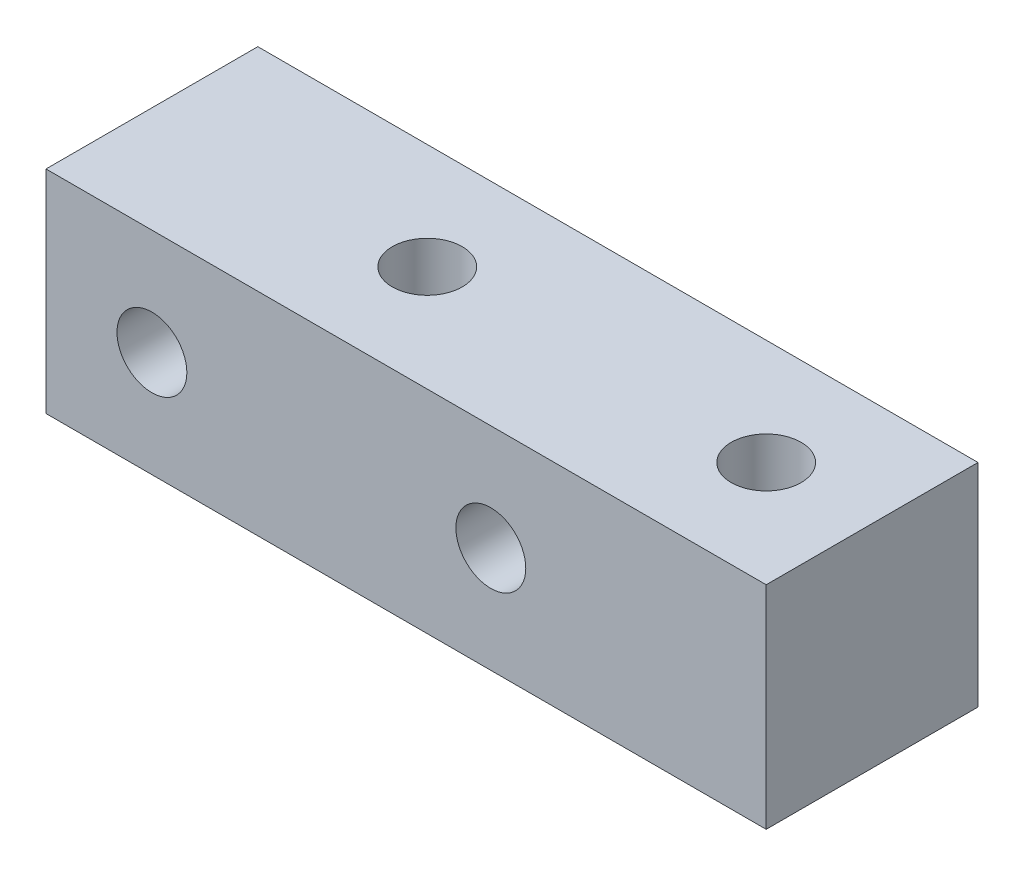
SolidWorks part; units mm, degrees
ref_plane "前视基准面" through (0, 0, 0) normal (0, 0, 1) x (1, 0, 0)
ref_plane "上视基准面" through (0, 0, 0) normal (0, 1, 0) x (1, 0, 0)
ref_plane "右视基准面" through (0, 0, 0) normal (1, 0, 0) x (0, 0, -1)
other "Configuration Table"
sketch "草图1" plane through (0, 0, 0) normal (0, 1, 0) x (1, 0, 0)
  line L1 (-17, 5) -> (17, 5)
  line L2 (-17, 5) -> (-17, -5)
  line L3 (-17, -5) -> (17, -5)
  line L4 (17, 5) -> (17, -5)
  line L5 (-17, 5) -> (17, -5) construction
  line L6 (-17, -5) -> (17, 5) construction
  point P0 (0, 0)
  dimension "D1" = 34
  dimension "D2" = 10
extrude "凸台-拉伸1" add sketch "草图1" along normal blind 10
sketch "草图2" plane through (0, 0, 5) normal (0, 0, 1) x (1, 0, 0)
  line L0 (-17, 5) -> (17, 5) construction
  line L1 (-17, 10) -> (-17, 0) construction
  line L2 (17, 10) -> (17, 0) construction
  point P6 (-12, 5)
  point P7 (4, 5)
  dimension "D1" = 16
  dimension "D2" = 5
sketch "草图4" plane through (0, 10, 0) normal (0, 1, 0) x (1, 0, 0)
  line L0 (-17, 0) -> (17, 0) construction
  line L1 (-17, 5) -> (-17, -5) construction
  line L2 (17, -5) -> (17, 5) construction
  point P6 (12, 0)
  point P7 (-4, 0)
  dimension "D1" = 5
  dimension "D2" = 16
hole_wizard "M4 螺纹孔1" positions "草图2" profile "草图3" tap size "M4" standard "GB" end condition through all
sketch "草图3" plane through (4, 5, 5) normal (1, 0, 0) x (0, -1, 0)
  line L0 (0, 0) -> (0, 10)
  line L1 (0, 10) -> (1.65, 10)
  line L2 (1.65, 10) -> (1.65, 0)
  line L5 (1.65, 0) -> (0, 0)
  line L11 (0, -6.35) -> (0, 107.95) construction
  dimension "通孔螺纹孔钻头直径" = 3.3
  dimension "通孔螺纹孔钻头深度" = 10
cosmetic thread "孔螺纹线1" parameters "D2"=4
cosmetic thread "孔螺纹线2" parameters "D2"=4
hole_wizard "M4 螺纹孔3" positions "草图4" profile "草图7" tap size "M4" standard "GB" end condition through all
sketch "草图7" plane through (-4, 10, 0) normal (1, 0, 0) x (0, 0, 1)
  line L0 (0, 0) -> (0, 10)
  line L1 (0, 10) -> (1.65, 10)
  line L2 (1.65, 10) -> (1.65, 0)
  line L5 (1.65, 0) -> (0, 0)
  line L11 (0, -6.35) -> (0, 107.95) construction
  dimension "通孔螺纹孔钻头直径" = 3.3
  dimension "通孔螺纹孔钻头深度" = 10
cosmetic thread "孔螺纹线5" parameters "D2"=4
cosmetic thread "孔螺纹线6" parameters "D2"=4
sketch "草图8" plane through (0, 10, 0) normal (0, 1, 0) x (1, 0, 0)
  circle A0 centre (-4, 0) radius 2.35
  circle A1 centre (12, 0) radius 2.35
  dimension "D1" = 4.7
extrude "切除-拉伸1" [suppressed] cut sketch "草图8" against normal blind 10
sketch "草图9" plane through (0, 0, -5) normal (0, 0, -1) x (-1, 0, 0)
  circle A0 centre (-4, 5) radius 2.35
  circle A1 centre (12, 5) radius 2.35
  dimension "D1" = 4.7
extrude "切除-拉伸2" [suppressed] cut sketch "草图9" against normal blind 10
